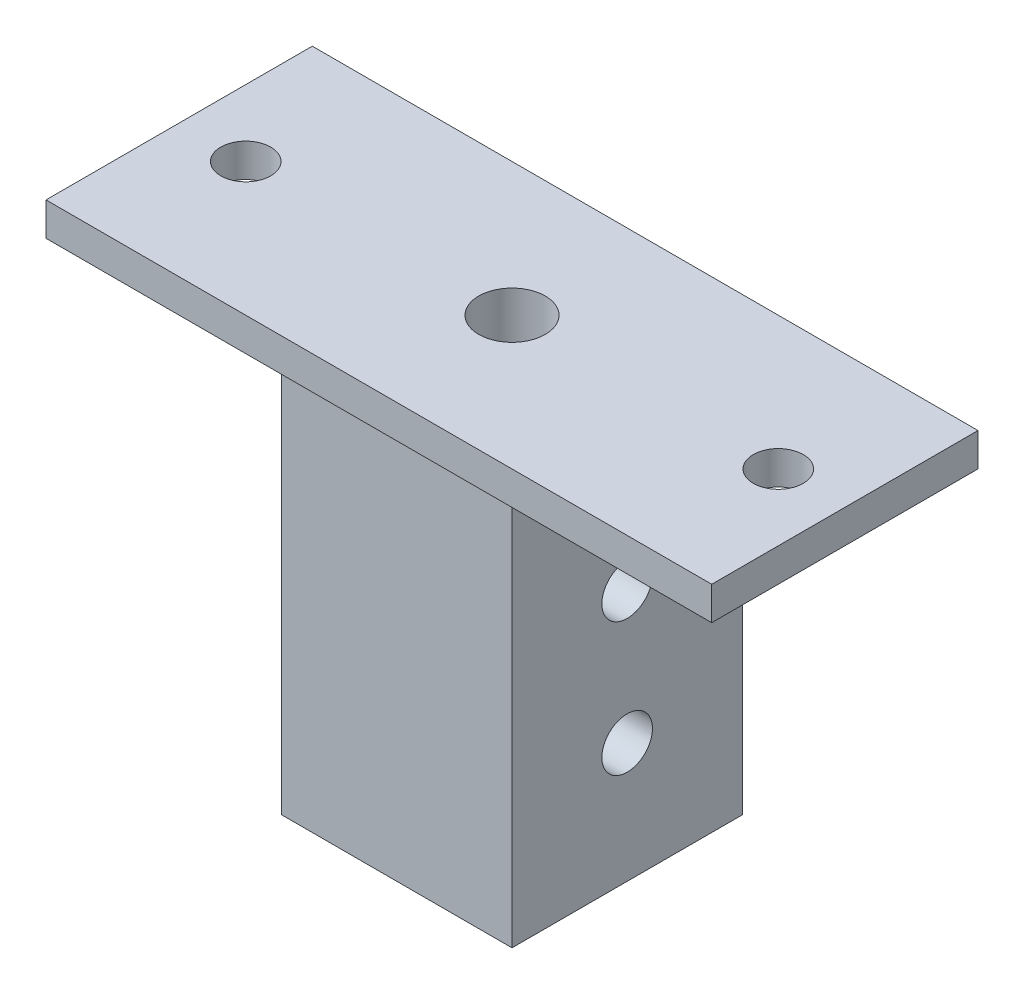
SolidWorks part; units mm, degrees
ref_plane "Front Plane" through (0, 0, 0) normal (0, 0, 1) x (1, 0, 0)
ref_plane "Top Plane" through (0, 0, 0) normal (0, 1, 0) x (1, 0, 0)
ref_plane "Right Plane" through (0, 0, 0) normal (1, 0, 0) x (0, 0, -1)
sketch "Sketch1" plane through (0, 0, 0) normal (0, 1, 0) x (1, 0, 0)
  line L1 (-10.9855, 10.9855) -> (10.9855, 10.9855)
  line L2 (-10.9855, 10.9855) -> (-10.9855, -10.9855)
  line L3 (-10.9855, -10.9855) -> (10.9855, -10.9855)
  line L4 (10.9855, 10.9855) -> (10.9855, -10.9855)
  line L5 (-10.9855, 10.9855) -> (10.9855, -10.9855) construction
  line L6 (-10.9855, -10.9855) -> (10.9855, 10.9855) construction
  point P0 (0, 0)
  dimension "D1" = 21.971
  dimension "D2" = 21.971
extrude "Boss-Extrude1" add sketch "Sketch1" along normal blind 38.1
sketch "Sketch2" plane through (0, 38.1, 0) normal (0, 1, 0) x (1, 0, 0)
  line L1 (-31.75, 12.7) -> (31.75, 12.7)
  line L2 (-31.75, 12.7) -> (-31.75, -12.7)
  line L3 (-31.75, -12.7) -> (31.75, -12.7)
  line L4 (31.75, 12.7) -> (31.75, -12.7)
  line L5 (-31.75, 12.7) -> (31.75, -12.7) construction
  line L6 (-31.75, -12.7) -> (31.75, 12.7) construction
  point P0 (0, 0)
  dimension "D1" = 25.4
  dimension "D2" = 63.5
extrude "Boss-Extrude2" add sketch "Sketch2" along normal blind 3.175
sketch "Sketch3" plane through (0, 41.275, 0) normal (0, 1, 0) x (1, 0, 0)
  circle A0 centre (0, 0) radius 25.4 construction
  circle A1 centre (25.4, 0) radius 2.3813
  circle A2 centre (-25.4, 0) radius 2.3813
  point P7 (-25.4, 0)
  dimension "D1" = 50.8
  dimension "D2" = 4.7625
  dimension "D3" = 4.7625
extrude "Cut-Extrude1" cut sketch "Sketch3" against normal blind 3.175
fillet "Fillet1" radius 1.27 4 edges at (0, 38.1, -10.9855) (-10.9855, 38.1, 0) (0, 38.1, 10.9855) (10.9855, 38.1, 0)
sketch "Sketch4" plane through (0, 41.275, 0) normal (0, 1, 0) x (1, 0, 0)
  circle A0 centre (0, 0) radius 3.175
  dimension "D1" = 6.35
extrude "Cut-Extrude2" cut sketch "Sketch4" against normal blind 15.24
sketch "Sketch5" plane through (10.9855, 0, 0) normal (1, 0, 0) x (0, 0, -1)
  line L0 (10.9855, 36.83) -> (-10.9855, 36.83) construction
  circle A0 centre (0, 24.13) radius 2.413
  circle A1 centre (0, 11.43) radius 2.413
  dimension "D3" = 4.826
  dimension "D4" = 4.826
  dimension "D1" = 12.7
  dimension "D2" = 12.7
extrude "Cut-Extrude3" cut sketch "Sketch5" against normal blind 25.4
